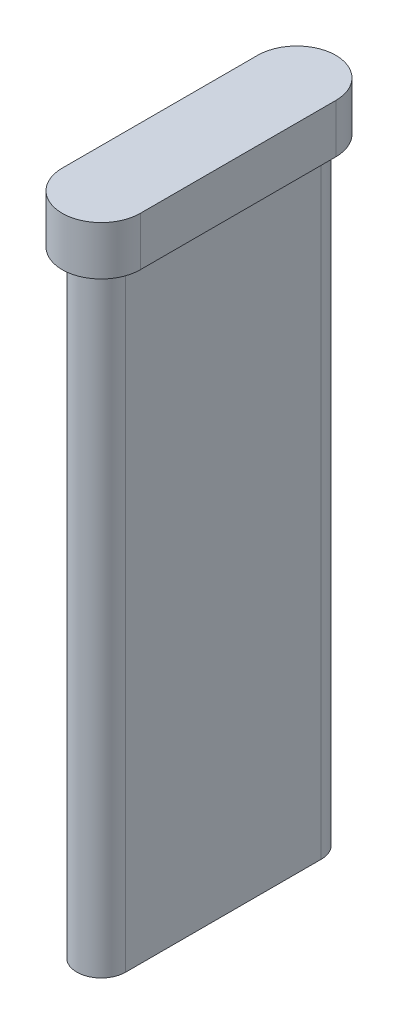
SolidWorks part; units mm, degrees
material "K110"
ref_plane "Front Plane" through (0, 0, 0) normal (0, 0, 1) x (1, 0, 0)
ref_plane "Top Plane" through (0, 0, 0) normal (0, 1, 0) x (1, 0, 0)
ref_plane "Right Plane" through (0, 0, 0) normal (1, 0, 0) x (0, 0, -1)
sketch "Sketch1" plane through (0, 0, 0) normal (0, 1, 0) x (1, 0, 0)
  line L0 (0, -10) -> (0, 10) construction
  line L1 (-2.5, -10) -> (-2.5, 10)
  line L2 (2.5, -10) -> (2.5, 10)
  arc A0 (-2.5, -10) -> (2.5, -10) centre (0, -10) ccw
  arc A1 (2.5, 10) -> (-2.5, 10) centre (0, 10) ccw
  point P2 (0, 0)
  dimension "D2" = 2.5
  dimension "D1" = 20
extrude "Boss-Extrude1" add sketch "Sketch1" against normal blind 68
sketch "Sketch2" plane through (0, 0, 0) normal (0, 1, 0) x (1, 0, 0)
  line L4 (4, -10) -> (4, 10)
  line L5 (-4, 10) -> (-4, -10)
  line L6 (4, -10) -> (4, 10)
  line L7 (-4, 10) -> (-4, -10)
  arc A4 (4, 10) -> (-4, 10) centre (0, 10) ccw
  arc A5 (-4, -10) -> (4, -10) centre (0, -10) ccw
  arc A6 (4, 10) -> (-4, 10) centre (0, 10) ccw
  arc A7 (-4, -10) -> (4, -10) centre (0, -10) ccw
  dimension "D1" = 1.5
extrude "Boss-Extrude2" add sketch "Sketch2" against normal blind 5
